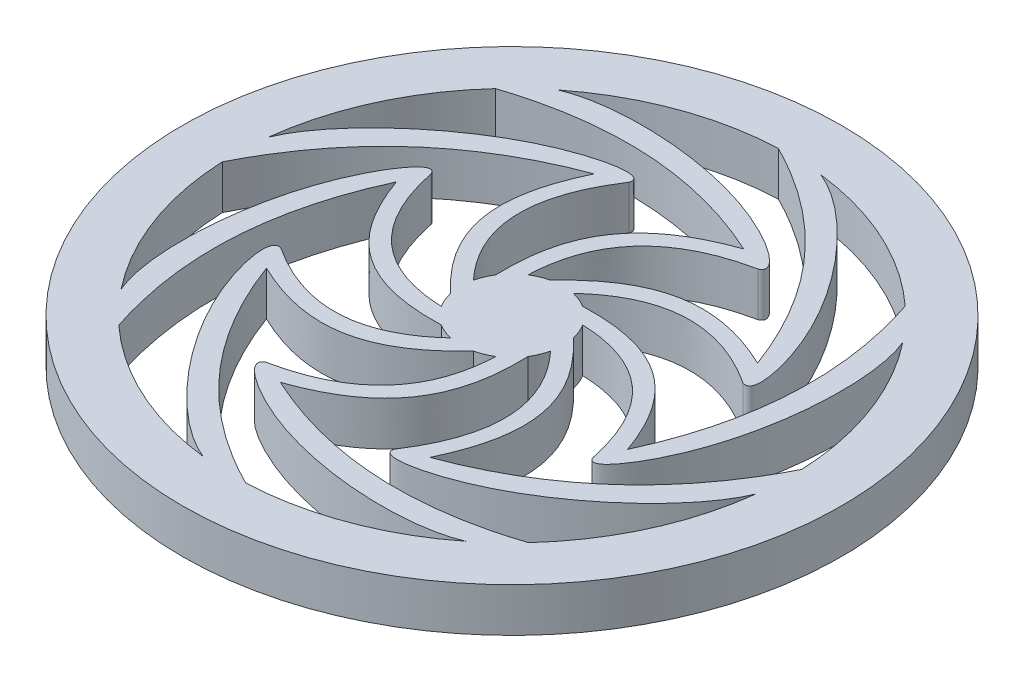
SolidWorks part; units mm, degrees
ref_plane "Front Plane" through (0, 0, 0) normal (0, 0, 1) x (1, 0, 0)
ref_plane "Top Plane" through (0, 0, 0) normal (0, 1, 0) x (1, 0, 0)
ref_plane "Right Plane" through (0, 0, 0) normal (1, 0, 0) x (0, 0, -1)
sketch "Sketch1" plane through (0, 0, 0) normal (0, 1, 0) x (1, 0, 0)
  circle A0 centre (0, 0) radius 22.5
  arc A1 (12.8583, 13.988) -> (2.2249, 18.8693) centre (0, 0) ccw
  arc A2 (0.7788, -3.4122) -> (1.8621, -2.9635) centre (0, 0) ccw
  circle A3 centre (0, 0) radius 12.5 construction
  arc A4 (-0.7989, 18.9832) -> (-11.7694, 14.9158) centre (0, 0) ccw
  arc A5 (-13.988, 12.8583) -> (-18.8693, 2.2249) centre (0, 0) ccw
  arc A6 (-18.9832, -0.7989) -> (-14.9158, -11.7694) centre (0, 0) ccw
  arc A7 (-12.8583, -13.988) -> (-2.2249, -18.8693) centre (0, 0) ccw
  arc A8 (0.7989, -18.9832) -> (11.7694, -14.9158) centre (0, 0) ccw
  arc A9 (13.988, -12.8583) -> (18.8693, -2.2249) centre (0, 0) ccw
  arc A10 (-1.8621, -2.9635) -> (-0.7788, -3.4122) centre (0, 0) ccw
  arc A11 (-3.4122, -0.7788) -> (-2.9635, -1.8621) centre (0, 0) ccw
  arc A12 (-2.9635, 1.8621) -> (-3.4122, 0.7788) centre (0, 0) ccw
  arc A13 (-0.7788, 3.4122) -> (-1.8621, 2.9635) centre (0, 0) ccw
  arc A14 (1.8621, 2.9635) -> (0.7788, 3.4122) centre (0, 0) ccw
  arc A15 (3.4122, 0.7788) -> (2.9635, 1.8621) centre (0, 0) ccw
  arc A16 (2.9635, -1.8621) -> (3.4122, -0.7788) centre (0, 0) ccw
  arc A17 (18.9832, 0.7989) -> (14.9158, 11.7694) centre (0, 0) ccw
  spline S0 degree 3 poles (-0.7788, 3.4122) (2.7849, 7.2287) (6.3642, 7.8741) (11.1857, 5.5794) knots 0 0 0 0 1 1 1 1
  spline S1 degree 2 poles (11.1857, 5.5794) (7.8394, 14.6362) (-0.7989, 18.9832) knots 0 0 0 1 1 1
  spline S2 degree 2 poles (0.7788, 3.4122) (5.6853, 7.968) (11.8756, 3.9014) knots 0 0 0 1 1 1
  spline S3 degree 3 poles (11.8756, 3.9014) (12.8896, 3.5053) (11.6139, 10.7888) (5.1518, 17.696) (2.2249, 18.8693) knots 0 0 0 0 0.363857 1 1 1 1
  spline S4 degree 3 poles (1.8621, 2.9635) (7.0807, 3.1423) (10.068, 1.0677) (11.8547, -3.9642) knots 0 0 0 0 1 1 1 1
  spline S5 degree 2 poles (2.9635, 1.8621) (9.6543, 1.6141) (11.156, -5.6386) knots 0 0 0 1 1 1
  spline S6 degree 3 poles (11.156, -5.6386) (11.593, -6.6357) (15.8411, -0.5835) (16.1558, 8.8701) (14.9158, 11.7694) knots 0 0 0 0 0.363857 1 1 1 1
  spline S7 degree 2 poles (11.8547, -3.9642) (15.8927, 4.8061) (12.8583, 13.988) knots 0 0 0 1 1 1
  spline S8 degree 3 poles (3.4122, 0.7788) (7.2287, -2.7849) (7.8741, -6.3642) (5.5794, -11.1857) knots 0 0 0 0 1 1 1 1
  spline S9 degree 2 poles (3.4122, -0.7788) (7.968, -5.6853) (3.9014, -11.8756) knots 0 0 0 1 1 1
  spline S10 degree 3 poles (3.9014, -11.8756) (3.5053, -12.8896) (10.7888, -11.6139) (17.696, -5.1518) (18.8693, -2.2249) knots 0 0 0 0 0.363857 1 1 1 1
  spline S11 degree 2 poles (5.5794, -11.1857) (14.6362, -7.8394) (18.9832, 0.7989) knots 0 0 0 1 1 1
  spline S12 degree 3 poles (2.9635, -1.8621) (3.1423, -7.0807) (1.0677, -10.068) (-3.9642, -11.8547) knots 0 0 0 0 1 1 1 1
  spline S13 degree 2 poles (1.8621, -2.9635) (1.6141, -9.6543) (-5.6386, -11.156) knots 0 0 0 1 1 1
  spline S14 degree 3 poles (-5.6386, -11.156) (-6.6357, -11.593) (-0.5835, -15.8411) (8.8701, -16.1558) (11.7694, -14.9158) knots 0 0 0 0 0.363857 1 1 1 1
  spline S15 degree 2 poles (-3.9642, -11.8547) (4.8061, -15.8927) (13.988, -12.8583) knots 0 0 0 1 1 1
  spline S16 degree 3 poles (0.7788, -3.4122) (-2.7849, -7.2287) (-6.3642, -7.8741) (-11.1857, -5.5794) knots 0 0 0 0 1 1 1 1
  spline S17 degree 2 poles (-0.7788, -3.4122) (-5.6853, -7.968) (-11.8756, -3.9014) knots 0 0 0 1 1 1
  spline S18 degree 3 poles (-11.8756, -3.9014) (-12.8896, -3.5053) (-11.6139, -10.7888) (-5.1518, -17.696) (-2.2249, -18.8693) knots 0 0 0 0 0.363857 1 1 1 1
  spline S19 degree 2 poles (-11.1857, -5.5794) (-7.8394, -14.6362) (0.7989, -18.9832) knots 0 0 0 1 1 1
  spline S20 degree 3 poles (-1.8621, -2.9635) (-7.0807, -3.1423) (-10.068, -1.0677) (-11.8547, 3.9642) knots 0 0 0 0 1 1 1 1
  spline S21 degree 2 poles (-2.9635, -1.8621) (-9.6543, -1.6141) (-11.156, 5.6386) knots 0 0 0 1 1 1
  spline S22 degree 3 poles (-11.156, 5.6386) (-11.593, 6.6357) (-15.8411, 0.5835) (-16.1558, -8.8701) (-14.9158, -11.7694) knots 0 0 0 0 0.363857 1 1 1 1
  spline S23 degree 2 poles (-11.8547, 3.9642) (-15.8927, -4.8061) (-12.8583, -13.988) knots 0 0 0 1 1 1
  spline S24 degree 3 poles (-3.4122, -0.7788) (-7.2287, 2.7849) (-7.8741, 6.3642) (-5.5794, 11.1857) knots 0 0 0 0 1 1 1 1
  spline S25 degree 2 poles (-3.4122, 0.7788) (-7.968, 5.6853) (-3.9014, 11.8756) knots 0 0 0 1 1 1
  spline S26 degree 3 poles (-3.9014, 11.8756) (-3.5053, 12.8896) (-10.7888, 11.6139) (-17.696, 5.1518) (-18.8693, 2.2249) knots 0 0 0 0 0.363857 1 1 1 1
  spline S27 degree 2 poles (-5.5794, 11.1857) (-14.6362, 7.8394) (-18.9832, -0.7989) knots 0 0 0 1 1 1
  spline S28 degree 3 poles (-2.9635, 1.8621) (-3.1423, 7.0807) (-1.0677, 10.068) (3.9642, 11.8547) knots 0 0 0 0 1 1 1 1
  spline S29 degree 2 poles (-1.8621, 2.9635) (-1.6141, 9.6543) (5.6386, 11.156) knots 0 0 0 1 1 1
  spline S30 degree 3 poles (5.6386, 11.156) (6.6357, 11.593) (0.5835, 15.8411) (-8.8701, 16.1558) (-11.7694, 14.9158) knots 0 0 0 0 0.363857 1 1 1 1
  spline S31 degree 2 poles (3.9642, 11.8547) (-4.8061, 15.8927) (-13.988, 12.8583) knots 0 0 0 1 1 1
  point P89 (0, 0)
  dimension "D1" = 45
  dimension "D2" = 38
  dimension "D3" = 7
  dimension "D4" = 25
extrude "Boss-Extrude1" add sketch "Sketch1" along normal blind 3
